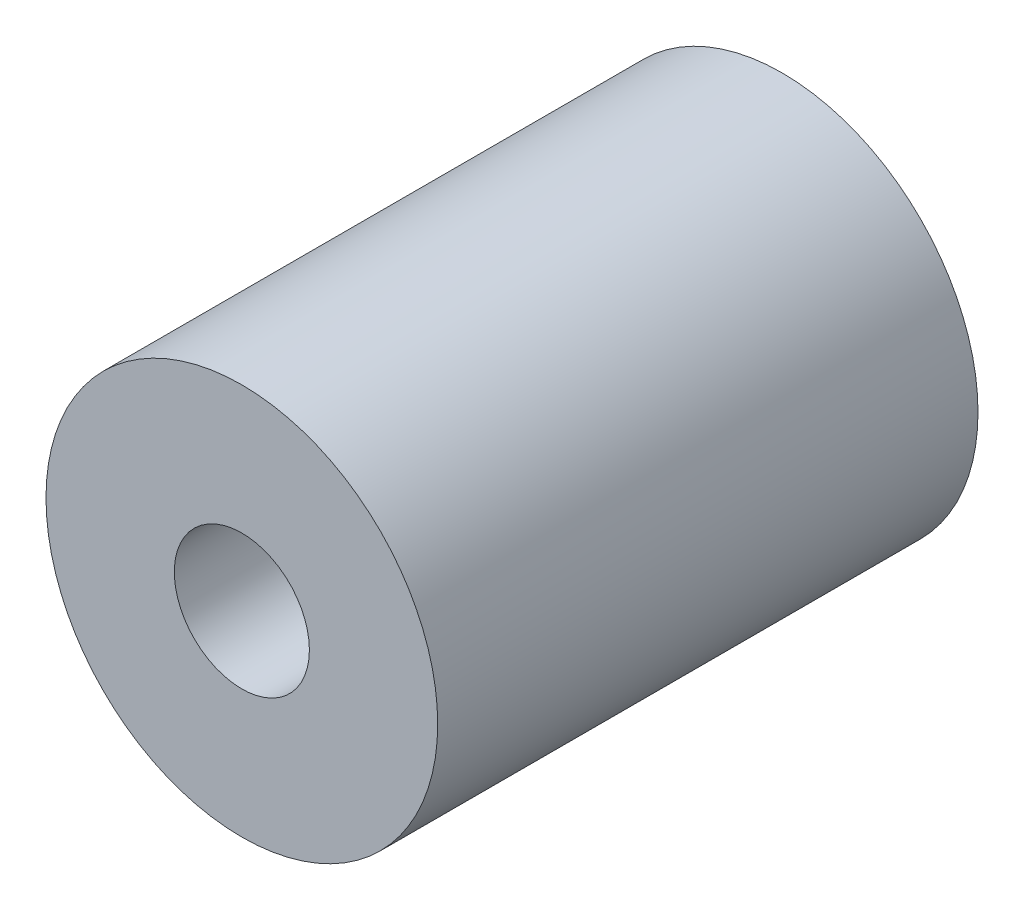
SolidWorks part; units mm, degrees
ref_plane "Front Plane" through (0, 0, 0) normal (0, 0, 1) x (1, 0, 0)
ref_plane "Top Plane" through (0, 0, 0) normal (0, 1, 0) x (1, 0, 0)
ref_plane "Right Plane" through (0, 0, 0) normal (1, 0, 0) x (0, 0, -1)
sketch "Sketch1" plane through (0, 0, 0) normal (0, 0, 1) x (1, 0, 0)
  circle A0 centre (0, 0) radius 2.9
  circle A1 centre (0, 0) radius 1
  dimension "D1" = 5.8
  dimension "D2" = 2
extrude "Boss-Extrude1" add sketch "Sketch1" along normal blind 8
